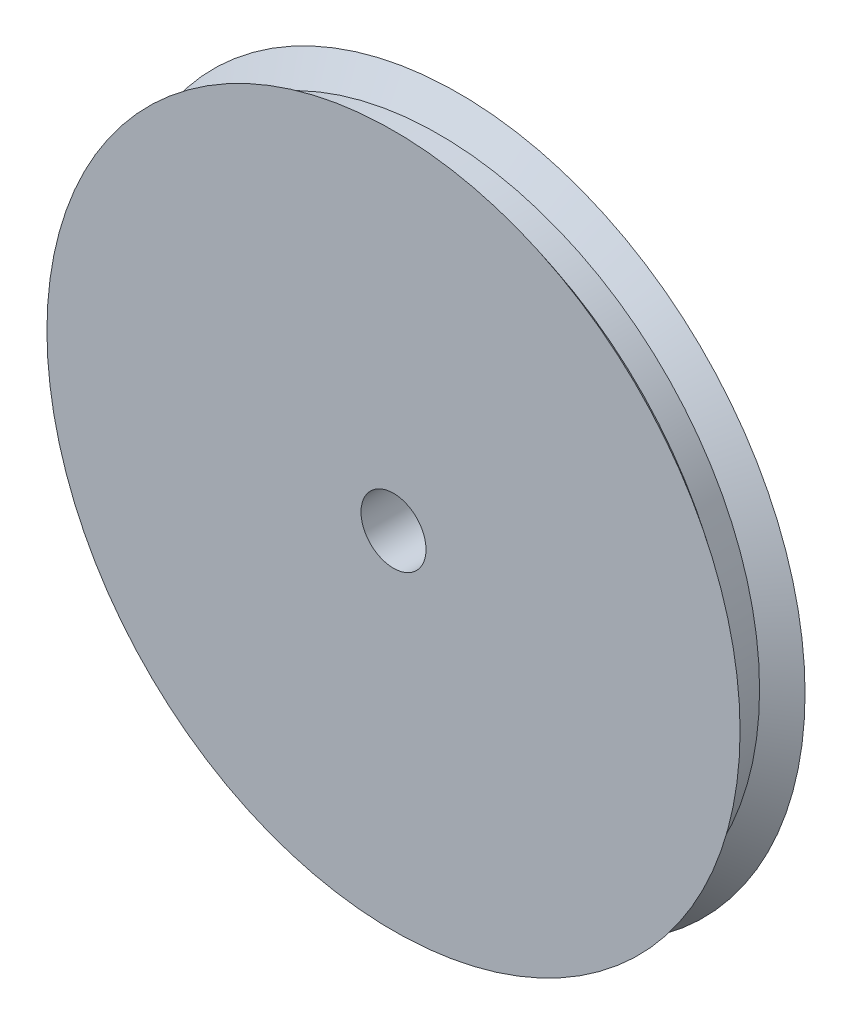
SolidWorks part; units mm, degrees
ref_plane "Front Plane" through (0, 0, 0) normal (0, 0, 1) x (1, 0, 0)
ref_plane "Top Plane" through (0, 0, 0) normal (0, 1, 0) x (1, 0, 0)
ref_plane "Right Plane" through (0, 0, 0) normal (1, 0, 0) x (0, 0, -1)
sketch "Sketch1" plane through (0, 0, 0) normal (0, 0, 1) x (1, 0, 0)
  circle A0 centre (0, 0) radius 101.6
  circle A1 centre (0, 0) radius 9.525
extrude "Boss-Extrude1" add sketch "Sketch1" along normal blind 19.05
sketch "Sketch2" plane through (0, 0, 0) normal (1, 0, 0) x (0, 0, -1)
  line L0 (0, 101.6) -> (-19.05, 101.6) construction
  line L1 (0, 101.6) -> (0, 104.8583)
  line L2 (0, 104.8583) -> (-19.05, 104.8583)
  line L3 (-19.05, 104.8583) -> (-19.05, 101.6)
  line L4 (0, 0) -> (-40.7903, 0) construction
  line L5 (-19.05, 101.6) -> (-13.335, 93.98)
  line L6 (-9.525, 104.8583) -> (-9.525, 93.98) construction
  line L7 (-13.335, 93.98) -> (-5.715, 93.98)
  line L8 (0, 101.6) -> (-5.715, 93.98)
  line L9 (-19.05, 101.6) -> (-9.525, 101.6)
  dimension "D1" = 10.8783
  dimension "D2" = 7.62
  dimension "D3" = 7.62
revolve "Cut-Revolve1" cut sketch "Sketch2" angle 360 about L4
sketch "Sketch3" plane through (0, 0, 0) normal (0, 0, -1) x (-1, 0, 0)
  circle A0 centre (0, 0) radius 15.24
  circle A1 centre (0, 0) radius 9.525 construction
  circle A2 centre (0, 0) radius 9.525
extrude "Boss-Extrude2" add sketch "Sketch3" along normal blind 6.35
ref_plane "Plane1" through (15.24, 0, 0) normal (1, 0, 0) x (0, 0, -1)
sketch "Sketch5" plane through (15.24, 0, 0) normal (1, 0, 0) x (0, 0, -1)
  line L0 (6.35, -15.24) -> (6.35, 15.24) construction
  circle A0 centre (3.175, 0) radius 1.27
  dimension "D1" = 3.175
extrude "Cut-Extrude1" cut sketch "Sketch5" against normal up to next
sketch "Sketch6" plane through (0, 0, 0) normal (1, 0, 0) x (0, 0, -1)
  line L0 (-19.05, 101.6) -> (-13.335, 93.98) construction
  line L1 (-13.335, 93.98) -> (-13.335, -93.98) construction
  line L2 (-13.335, 93.98) -> (-19.05, 101.6) construction
  line L3 (-13.335, 93.98) -> (-5.715, 93.98) construction
  line L4 (-5.715, 93.98) -> (0, 101.6) construction
  line L5 (0, 101.6) -> (-19.05, 101.6) construction
